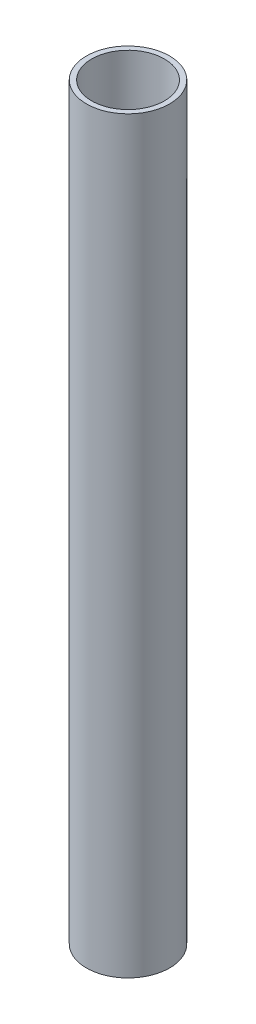
SolidWorks part; units mm, degrees
material "6061-T6 (SS)"
ref_plane "Front Plane" through (0, 0, 0) normal (0, 0, 1) x (1, 0, 0)
ref_plane "Top Plane" through (0, 0, 0) normal (0, 1, 0) x (1, 0, 0)
ref_plane "Right Plane" through (0, 0, 0) normal (1, 0, 0) x (0, 0, -1)
sketch "Sketch1" plane through (0, 0, 0) normal (0, 1, 0) x (1, 0, 0)
  circle A0 centre (0, 0) radius 25.4
  circle A1 centre (0, 0) radius 22.225
  dimension "D1" = 50.8
  dimension "D2" = 3.175
extrude "Boss-Extrude1" add sketch "Sketch1" along normal blind 457.2
